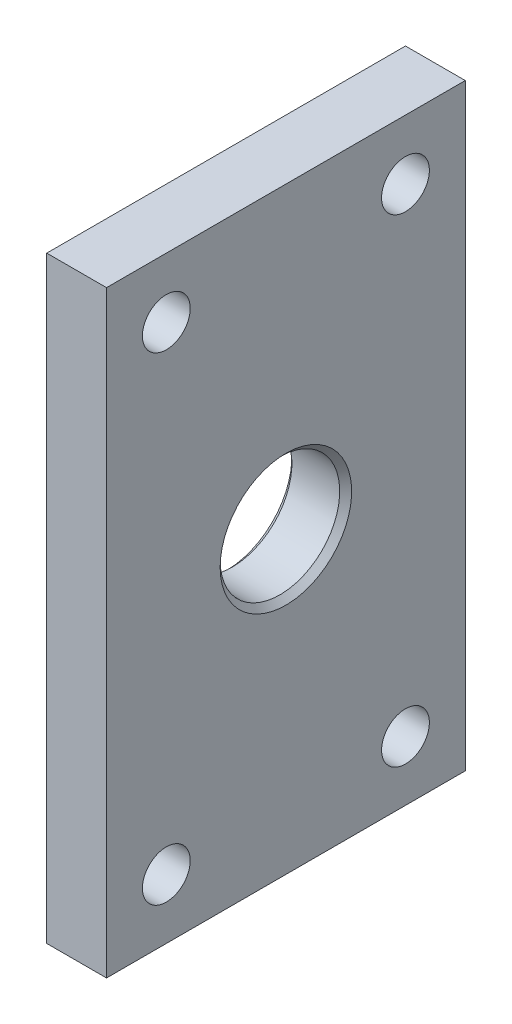
SolidWorks part; units mm, degrees
ref_plane "Front Plane" through (0, 0, 0) normal (1, 0, 0) x (0, 1, 0)
ref_plane "Top Plane" through (0, 0, 0) normal (0, 0, 1) x (0, 1, 0)
ref_plane "Right Plane" through (0, 0, 0) normal (0, 1, 0) x (-1, 0, 0)
sketch "Sketch1" plane through (0, 0, 0) normal (1, 0, 0) x (0, 1, 0)
  line L1 (0, 0) -> (100, 0)
  line L2 (0, 0) -> (0, 60)
  line L3 (0, 60) -> (100, 60)
  line L4 (100, 0) -> (100, 60)
extrude "Boss-Extrude1" add sketch "Sketch1" along normal blind 10
sketch "Sketch2" plane through (0, 0, 0) normal (1, 0, 0) x (0, 1, 0)
  circle A0 centre (10, 10) radius 4
  circle A1 centre (90, 10) radius 4
  circle A2 centre (10, 50) radius 4
  circle A3 centre (90, 50) radius 4
extrude "Cut-Extrude2" cut sketch "Sketch2" along normal through all
sketch "Sketch3" plane through (0, 0, 0) normal (1, 0, 0) x (0, 1, 0)
  circle A0 centre (50, 30) radius 10
extrude "Cut-Extrude4" cut sketch "Sketch3" along normal through all
chamfer "Chamfer1" distance 1 angle 45 2 edges at (0, 50, 20) (10, 50, 20)
